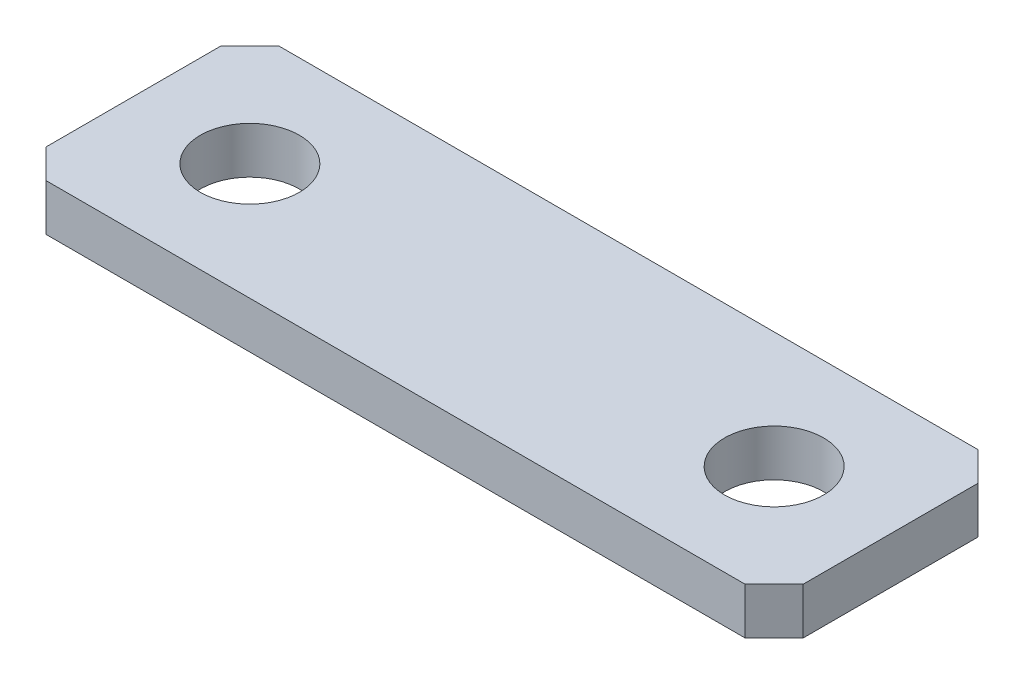
SolidWorks part; units mm, degrees
ref_plane "前视基准面" through (0, 0, 0) normal (0, 0, 1) x (1, 0, 0)
ref_plane "上视基准面" through (0, 0, 0) normal (0, 1, 0) x (1, 0, 0)
ref_plane "右视基准面" through (0, 0, 0) normal (1, 0, 0) x (0, 0, -1)
sketch "草图1" plane through (0, 0, 0) normal (0, 1, 0) x (1, 0, 0)
  line L0 (-1000, 20) -> (49000, 20) construction
  line L1 (0, 0) -> (130, 0)
  line L2 (0, 0) -> (0, 40)
  line L3 (0, 40) -> (130, 40)
  line L4 (130, 0) -> (130, 40)
  line L5 (65, -960) -> (65, 49040) construction
  circle A0 centre (20, 20) radius 8.5
  circle A1 centre (110, 20) radius 8.5
  point P8 (0, 20)
  point P11 (65, 40)
  dimension "D3" = 17
  dimension "D4" = 17
  dimension "D1" = 130
  dimension "D2" = 40
  dimension "D5" = 90
extrude "凸台-拉伸1" add sketch "草图1" along normal blind 8
chamfer "倒角1" distance 5 angle 45 4 edges at (0, 4, -40) (130, 4, -40) (130, 4, 0) (0, 4, 0)
